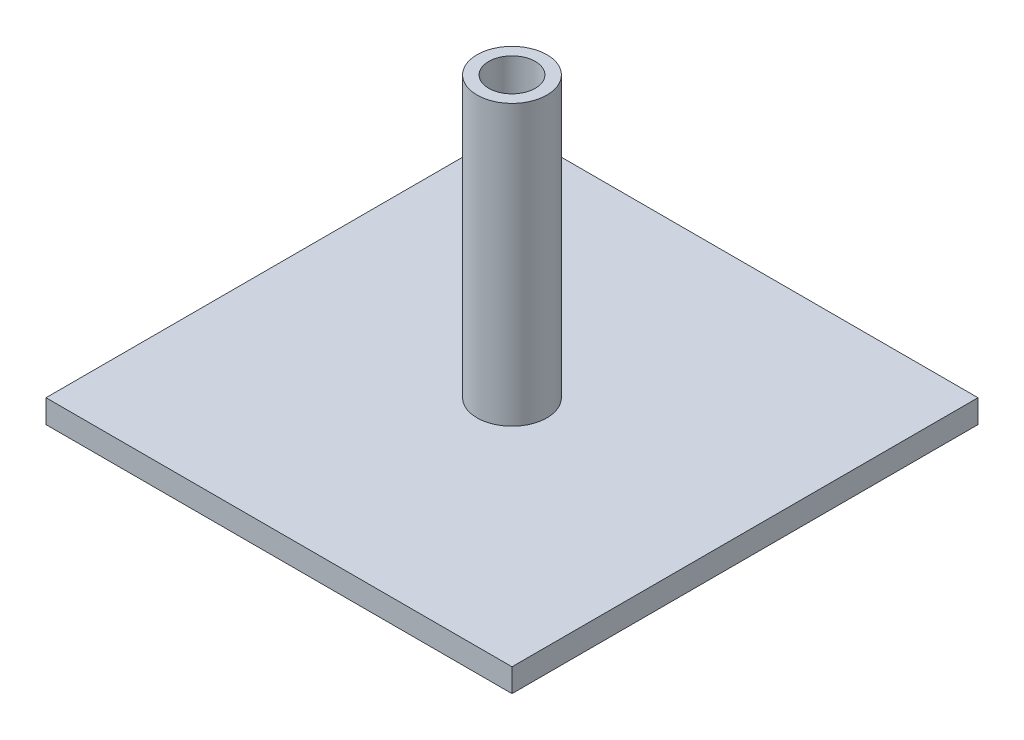
SolidWorks part; units mm, degrees
ref_plane "Plano frontal" through (0, 0, 0) normal (0, 0, 1) x (1, 0, 0)
ref_plane "Plano superior" through (0, 0, 0) normal (0, 1, 0) x (1, 0, 0)
ref_plane "Plano direito" through (0, 0, 0) normal (1, 0, 0) x (0, 0, -1)
sketch "Esboço1" plane through (0, 0, 0) normal (0, 1, 0) x (1, 0, 0)
  line L1 (-50, 50) -> (50, 50)
  line L2 (-50, 50) -> (-50, -50)
  line L3 (-50, -50) -> (50, -50)
  line L4 (50, 50) -> (50, -50)
  line L5 (-50, 50) -> (50, -50) construction
  line L6 (-50, -50) -> (50, 50) construction
  point P0 (0, 0)
  dimension "D1" = 100
  dimension "D2" = 100
extrude "Ressalto-extrusão1" add sketch "Esboço1" against normal blind 5
sketch "Esboço2" plane through (0, 0, 0) normal (0, 1, 0) x (1, 0, 0)
  line L0 (0, 0) -> (0, 5) construction
  circle A0 centre (0, 0) radius 7.5
  circle A1 centre (0, 0) radius 5
  dimension "D1" = 15
  dimension "D2" = 2.5
  dimension "D3" = 10
extrude "Ressalto-extrusão2" add sketch "Esboço2" along normal blind 60
